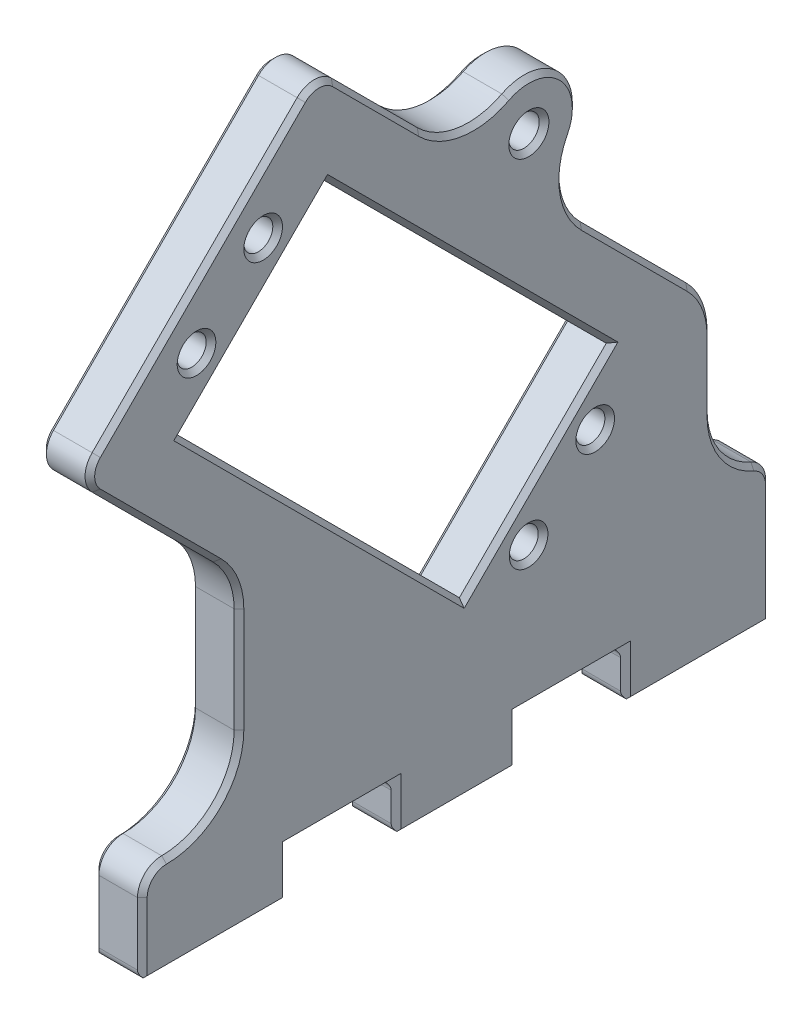
SolidWorks part; units mm, degrees
ref_plane "前视基准面" through (0, 0, 0) normal (0, 0, 1) x (1, 0, 0)
ref_plane "上视基准面" through (0, 0, 0) normal (0, 1, 0) x (1, 0, 0)
ref_plane "右视基准面" through (0, 0, 0) normal (1, 0, 0) x (0, 0, -1)
ref_plane "基准面1" through (5, 0, 0) normal (1, 0, 0) x (0, 0, -1)
sketch "草图1" plane through (5, 0, 0) normal (1, 0, 0) x (0, 0, -1)
  line L0 (19.1656, 62.2739) -> (48.5105, 32.9289)
  line L1 (48.5105, 32.9289) -> (33.3077, 17.7261)
  line L2 (33.3077, 17.7261) -> (3.9628, 47.0711)
  line L3 (3.9628, 47.0711) -> (19.1656, 62.2739)
  line L4 (58.9404, 21.6909) -> (58.9404, 28.9384)
  line L5 (56.7437, 34.2417) -> (45.7979, 45.1876)
  line L6 (28.9509, 62.0345) -> (20.0495, 70.9359)
  line L7 (16.514, 70.9359) -> (-4.6992, 49.7227)
  line L8 (-4.6992, 46.1872) -> (7.8033, 33.6846)
  line L9 (10, 28.3813) -> (10, 17.5)
  line L10 (0, 7.5) -> (0, 0)
  line L11 (0, 0) -> (15, 0)
  line L12 (15, 0) -> (15, 5)
  line L13 (15, 5) -> (26.25, 5)
  line L14 (26.25, 5) -> (26.25, 0)
  line L15 (26.25, 0) -> (38.75, 0)
  line L16 (38.75, 0) -> (38.75, 5)
  line L17 (38.75, 5) -> (50, 5)
  line L18 (50, 5) -> (50, 0)
  line L19 (50, 0) -> (65, 0)
  line L20 (65, 0) -> (65, 12.5)
  circle A0 centre (40, 56.2367) radius 1.575
  circle A1 centre (39.9722, 19.3702) radius 1.5
  arc A2 (65, 12.5) -> (63.4851, 14.7977) centre (62.5, 12.5) ccw
  arc A3 (63.4851, 14.7977) -> (58.9404, 21.6909) centre (66.4404, 21.6909) cw
  arc A4 (58.9404, 28.9384) -> (56.7437, 34.2417) centre (51.4404, 28.9384) ccw
  arc A5 (45.7979, 45.1876) -> (44.4405, 53.9384) centre (51.1012, 50.4909) cw
  arc A6 (44.4405, 53.9384) -> (37.7017, 60.6771) centre (40, 56.2367) ccw
  arc A7 (37.7017, 60.6771) -> (28.9509, 62.0345) centre (34.2542, 67.3378) cw
  arc A8 (20.0495, 70.9359) -> (16.514, 70.9359) centre (18.2817, 69.1682) ccw
  arc A9 (-4.6992, 49.7227) -> (-4.6992, 46.1872) centre (-2.9315, 47.955) ccw
  arc A10 (7.8033, 33.6846) -> (10, 28.3813) centre (2.5, 28.3813) cw
  arc A11 (10, 17.5) -> (2.5, 10) centre (2.5, 17.5) cw
  arc A12 (2.5, 10) -> (0, 7.5) centre (2.5, 7.5) ccw
  circle A13 centre (12.5011, 60.6298) radius 1.5
  circle A14 centre (5.6068, 53.7355) radius 1.5
  circle A15 centre (46.8665, 26.2645) radius 1.5
extrude "凸台-拉伸1" add sketch "草图1" against normal blind 5
chamfer "倒角1" distance 0.5 angle 45 74 edges at (0, 17.5627, -60.1788) (0, 25.3147, -58.9404) (0, 31.8086, -58.3695) (0, 39.7147, -51.2708) (0, 49.3412, -43.6898) (0, 59.7722, -43.5355) (0, 59.9265, -33.1046) (0, 66.4852, -24.5002) (0, 71.6682, -18.2817) (0, 60.3293, -5.9074) (0, 47.955, 5.4315) (0, 39.9359, -1.552) (0, 31.2515, -9.4291) (0, 22.9407, -10) (0, 12.1967, -7.8033) (0, 9.2678, -0.7322) (0, 3.75, 0) (0, 0, -7.5) (0, 2.5, -15) (0, 5, -20.625) (0, 2.5, -26.25) (0, 0, -32.5) (0, 2.5, -38.75) (0, 5, -44.375) (0, 2.5, -50) (0, 0, -57.5) (0, 6.25, -65) (0, 13.8761, -64.5872) (0, 56.2367, -38.425) (0, 19.3702, -38.4722) (0, 25.3275, -40.9091) (0, 32.3986, -18.6353) (0, 54.6725, -11.5642) (0, 47.6014, -33.8381) (0, 60.6298, -11.0011) (0, 53.7355, -4.1068) (0, 26.2645, -45.3665) (5, 6.25, -65) (5, 0, -57.5) (5, 2.5, -50) (5, 5, -44.375) (5, 2.5, -38.75) (5, 0, -32.5) (5, 2.5, -26.25) (5, 5, -20.625) (5, 2.5, -15) (5, 0, -7.5) (5, 3.75, 0) (5, 9.2678, -0.7322) (5, 12.1967, -7.8033) (5, 22.9407, -10) (5, 31.2515, -9.4291) (5, 39.9359, -1.552) (5, 47.955, 5.4315) (5, 60.3293, -5.9074) (5, 71.6682, -18.2817) (5, 66.4852, -24.5002) (5, 59.9265, -33.1046) (5, 59.7722, -43.5355) (5, 49.3412, -43.6898) (5, 39.7147, -51.2708) (5, 31.8086, -58.3695) (5, 25.3147, -58.9404) (5, 17.5627, -60.1788) (5, 13.8761, -64.5872) (5, 56.2367, -38.425) (5, 19.3702, -38.4722) (5, 32.3986, -18.6353) (5, 25.3275, -40.9091) (5, 47.6014, -33.8381) (5, 54.6725, -11.5642) (5, 60.6298, -11.0011) (5, 53.7355, -4.1068) (5, 26.2645, -45.3665)
fillet "圆角1" radius 1 10 edges at (2.5, 0, 0) (2.5, 0, -15) (2.5, 5, -15) (2.5, 0, -26.25) (2.5, 5, -26.25) (2.5, 0, -38.75) (2.5, 5, -38.75) (2.5, 5, -50) (2.5, 0, -50) (2.5, 0, -65)
